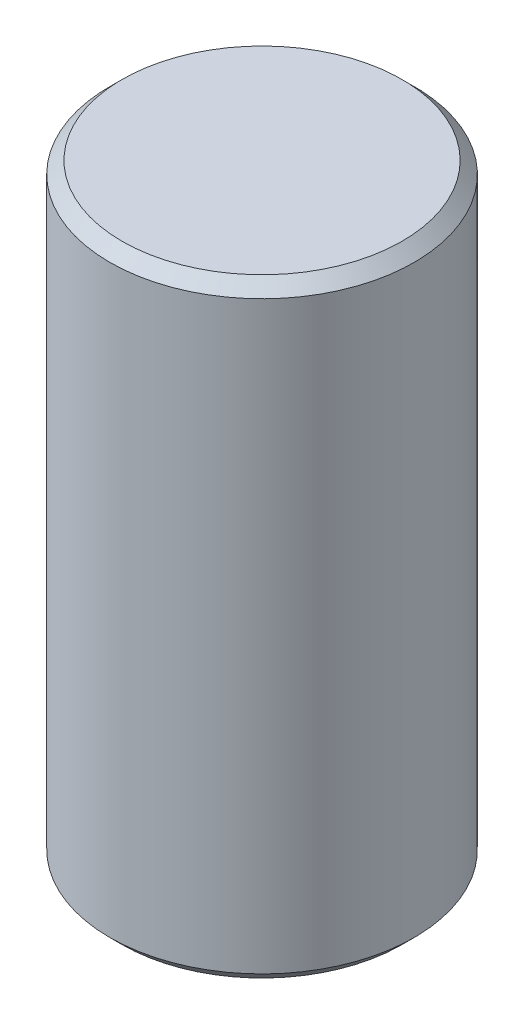
SolidWorks part; units mm, degrees
ref_plane "Front Plane" through (0, 0, 0) normal (0, 0, 1) x (1, 0, 0)
ref_plane "Top Plane" through (0, 0, 0) normal (0, 1, 0) x (1, 0, 0)
ref_plane "Right Plane" through (0, 0, 0) normal (1, 0, 0) x (0, 0, -1)
sketch "Sketch1" plane through (0, 0, 0) normal (0, 1, 0) x (1, 0, 0)
  circle A0 centre (0, 0) radius 1.25
  dimension "D1" = 2.5
extrude "Boss-Extrude1" add sketch "Sketch1" along normal mid plane 5
chamfer "Chamfer1" distance 0.1 angle 45 2 edges at (0, -2.5, 1.25) (0, 2.5, 1.25)
